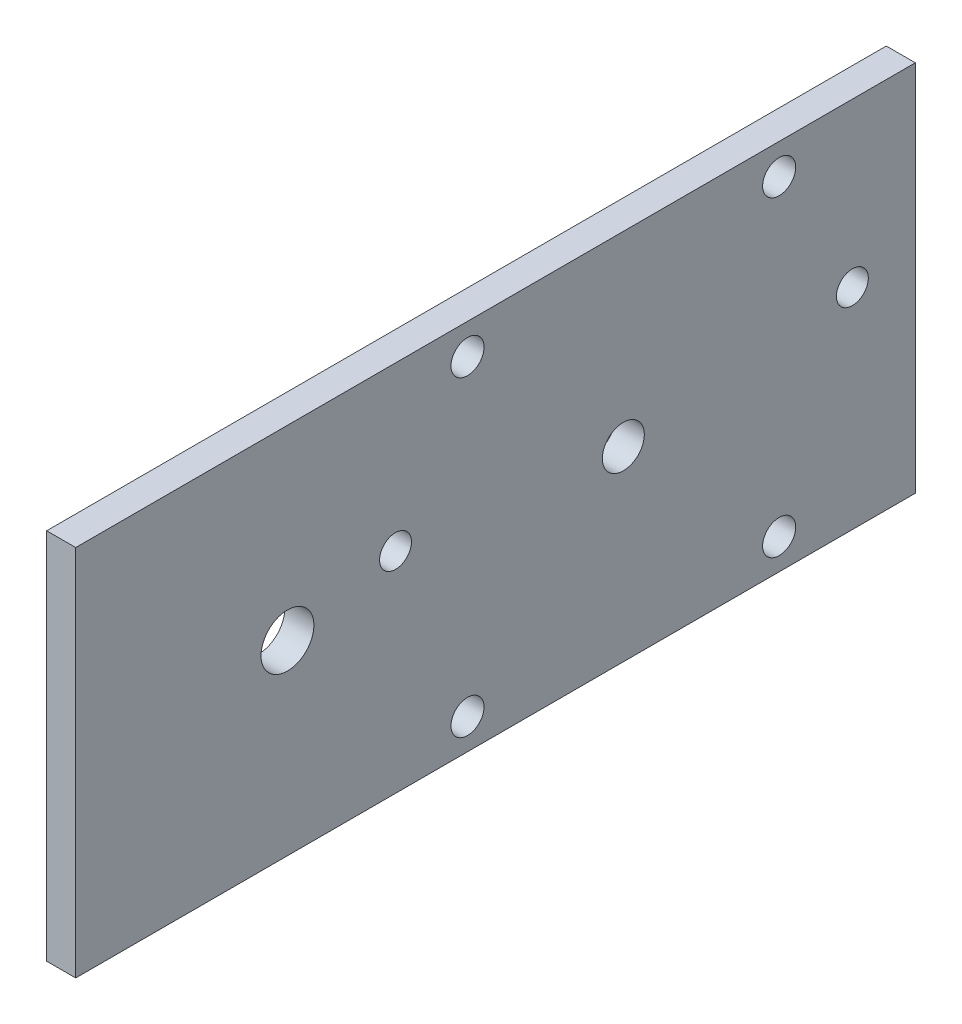
SolidWorks part; units mm, degrees
ref_plane "Front Plane" through (0, 0, 0) normal (0, 0, 1) x (1, 0, 0)
ref_plane "Top Plane" through (0, 0, 0) normal (0, 1, 0) x (1, 0, 0)
ref_plane "Right Plane" through (0, 0, 0) normal (1, 0, 0) x (0, 0, -1)
sketch "Sketch2" plane through (0, 0, 0) normal (0, 0, 1) x (1, 0, 0)
  line L0 (0, 0) -> (0, 56.388)
  line L1 (0, 56.388) -> (4.3942, 56.388)
  line L2 (4.3942, 56.388) -> (4.3942, 0)
  line L5 (4.3942, 0) -> (0, 0)
  dimension "D1" = 4.3942
  dimension "D4" = 56.388
extrude "Boss-Extrude1" add sketch "Sketch2" along normal blind 127
sketch "Sketch4" plane through (0, 0, 0) normal (-1, 0, 0) x (0, 0, 1)
  line L0 (0, 56.388) -> (0, 0) construction
  line L1 (127, 56.388) -> (0, 56.388) construction
  line L2 (127, 0) -> (0, 0) construction
  line L3 (44.1706, 0) -> (44.1706, 56.388) construction
  line L4 (44.1706, 28.2) -> (127, 28.2) construction
  line L5 (127, 56.388) -> (127, 0) construction
  circle A0 centre (20.5994, 4.63) radius 2.5
  circle A1 centre (9.525, 31.75) radius 2.413
  circle A2 centre (67.7394, 4.63) radius 2.5
  circle A3 centre (78.625, 31.75) radius 2.413
  circle A4 centre (44.1706, 28.2) radius 3.175
  circle A5 centre (94.9706, 28.2) radius 4
  circle A6 centre (67.7394, 51.7724) radius 2.5
  circle A7 centre (20.5994, 51.7724) radius 2.5
  dimension "D1" = 5
  dimension "D2" = 6.35
  dimension "D7" = 4.826
  dimension "D12" = 8
  dimension "D3" = 47.14
  dimension "D4" = 69.1
  dimension "D5" = 9.525
  dimension "D6" = 24.638
  dimension "D8" = 4.63
  dimension "D9" = 44.1706
  dimension "D10" = 47.1424
  dimension "D11" = 23.57
  dimension "D13" = 50.8
  dimension "D14" = 47.1424
extrude "Cut-Extrude2" cut sketch "Sketch4" against normal through all
